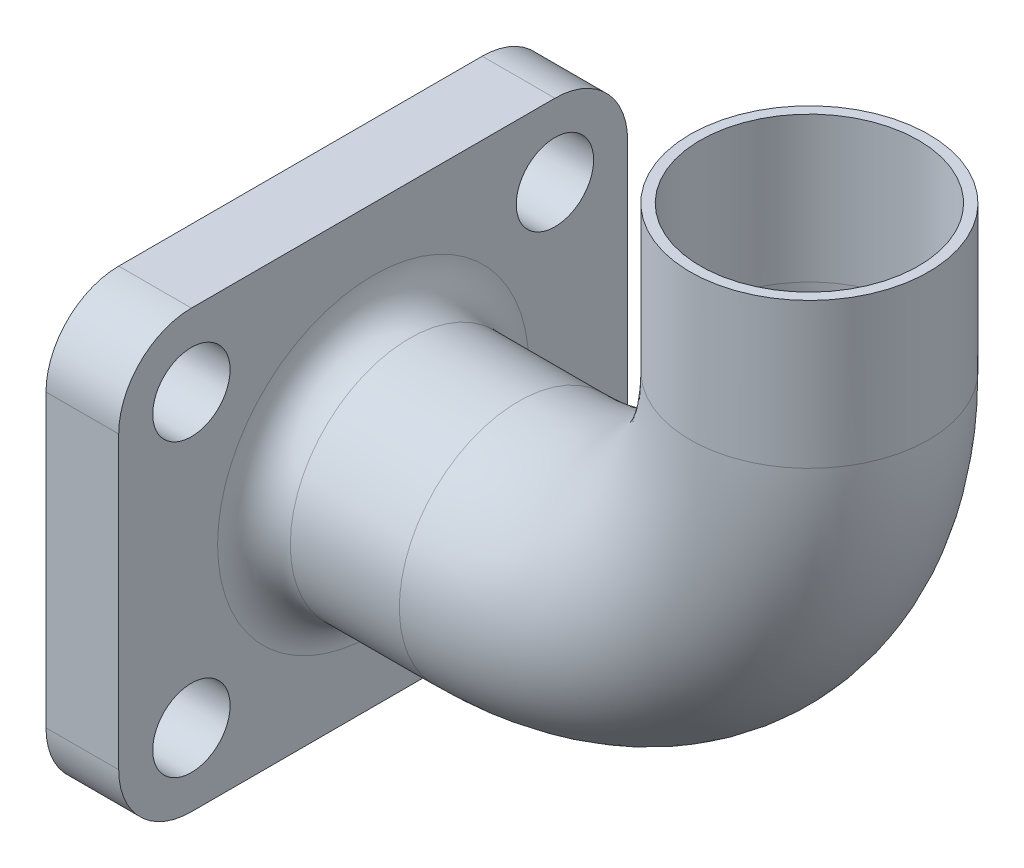
SolidWorks part; units mm, degrees
material "Chrome Stainless Steel"
ref_plane "Front" through (0, 0, 0) normal (0, 0, 1) x (1, 0, 0)
ref_plane "Top" through (0, 0, 0) normal (0, 1, 0) x (1, 0, 0)
ref_plane "Right" through (0, 0, 0) normal (1, 0, 0) x (0, 0, -1)
sketch "Sketch1" plane through (0, 0, 0) normal (1, 0, 0) x (0, 0, -1)
  line L1 (-15.875, -19.05) -> (15.875, -19.05)
  line L2 (-22.225, -12.7) -> (-22.225, 12.7)
  line L3 (-15.875, 19.05) -> (15.875, 19.05)
  line L4 (22.225, -12.7) -> (22.225, 12.7)
  line L5 (-22.225, -19.05) -> (22.225, 19.05) construction
  line L6 (-22.225, 19.05) -> (22.225, -19.05) construction
  arc A0 (-15.875, -19.05) -> (-22.225, -12.7) centre (-15.875, -12.7) cw
  arc A1 (15.875, -19.05) -> (22.225, -12.7) centre (15.875, -12.7) ccw
  arc A2 (15.875, 19.05) -> (22.225, 12.7) centre (15.875, 12.7) cw
  arc A3 (-22.225, 12.7) -> (-15.875, 19.05) centre (-15.875, 12.7) cw
  circle A4 centre (0, 0) radius 9.525
  point P0 (0, 0)
  dimension "D3" = 6.35
  dimension "D4" = 19.05
  dimension "D1" = 38.1
  dimension "D2" = 44.45
extrude "Boss-Extrude1" add sketch "Sketch1" along normal blind 6.35
sketch "Sketch2" plane through (0, 0, 0) normal (0, 0, 1) x (1, 0, 0)
  line L0 (0, 0) -> (19.05, 0)
  line L1 (44.45, 25.4) -> (44.45, 38.1)
  line L2 (6.35, 12.7) -> (6.35, -12.7) construction
  arc A0 (19.05, 0) -> (44.45, 25.4) centre (19.05, 25.4) ccw
  dimension "D3" = 25.4
  dimension "D1" = 38.1
  dimension "D2" = 38.1
sketch "Sketch3" plane through (6.35, 0, 0) normal (1, 0, 0) x (0, 0, -1)
  circle A0 centre (0, 0) radius 9.525 construction
  circle A1 centre (0, 0) radius 9.525
sweep "Sweep-Thin1" add profiles "Sketch3" path "Sketch2" parameters "D1"=0.889
sketch "Sketch4" plane through (0, 0, 0) normal (-1, 0, 0) x (0, 0, 1)
  circle A0 centre (0, 0) radius 9.525 construction
  circle A1 centre (0, 0) radius 9.525
  circle A2 centre (0, 0) radius 12.7
  dimension "D1" = 25.4
extrude "Boss-Extrude2" add sketch "Sketch4" along normal blind 2.921
fillet "Fillet1" radius 3.175 1 edges at (6.35, 0, -10.414)
hole_wizard "1/4 Clearance Hole1" positions "Sketch6" profile "Sketch5" hole size "1/4" standard "ANSI Inch" end condition through all
sketch "Sketch6" plane through (6.35, 0, 0) normal (1, 0, 0) x (0, 0, -1)
  point P0 (-15.875, 12.7)
  point P3 (15.875, 12.7)
  point P6 (15.875, -12.7)
  point P9 (-15.875, -12.7)
sketch "Sketch5" plane through (6.35, 12.7, 15.875) normal (0, 1, 0) x (0, 0, -1)
  line L0 (0, 0) -> (0, 9.271)
  line L1 (0, 9.271) -> (3.3782, 9.271)
  line L2 (3.3782, 9.271) -> (3.3782, 0)
  line L5 (3.3782, 0) -> (0, 0)
  line L11 (0, -6.35) -> (0, 107.95) construction
  dimension "Thru Hole Dia." = 6.7564
  dimension "Thru Hole Depth" = 9.271
